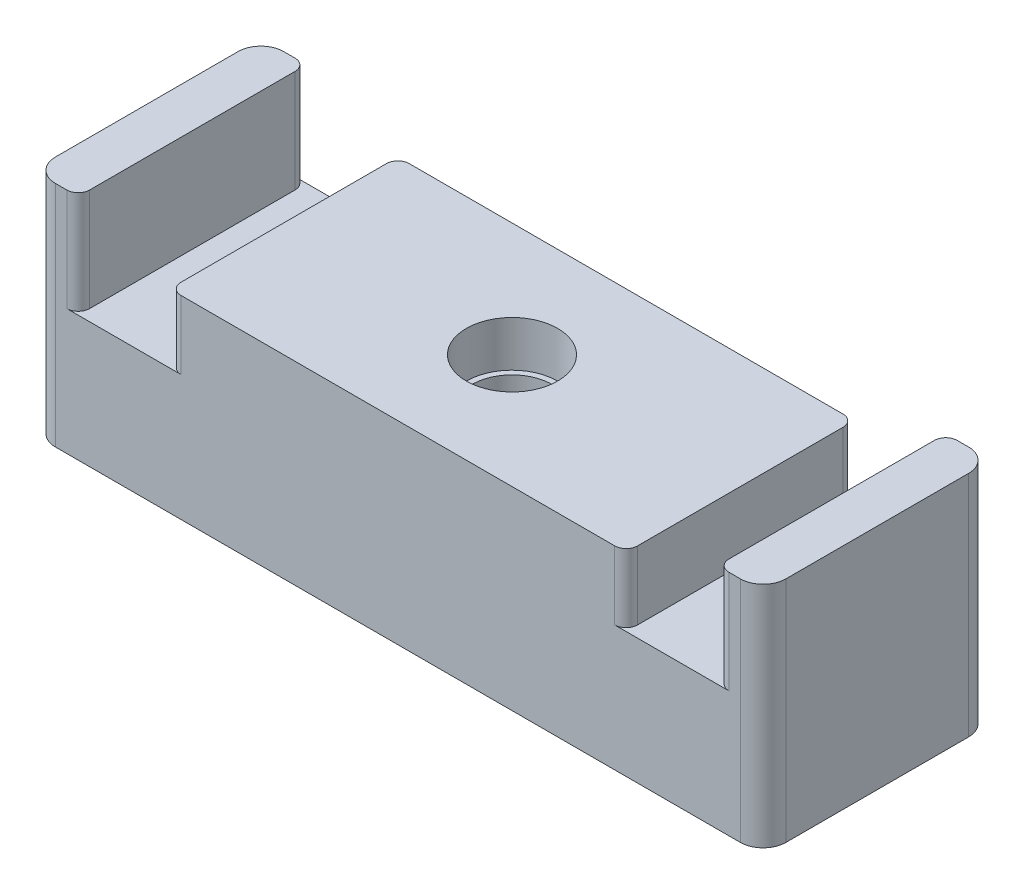
SolidWorks part; units mm, degrees
ref_plane "Front Plane" through (0, 0, 0) normal (0, 0, 1) x (1, 0, 0)
ref_plane "Top Plane" through (0, 0, 0) normal (0, 1, 0) x (1, 0, 0)
ref_plane "Right Plane" through (0, 0, 0) normal (1, 0, 0) x (0, 0, -1)
sketch "Sketch1" plane through (0, 0, 0) normal (0, 0, 1) x (1, 0, 0)
  line L0 (12, 0) -> (-12, 0) construction
  line L1 (-10, 2.5) -> (10, 2.5)
  line L2 (-16, 2.5) -> (-16, -7.5)
  line L3 (-16, -7.5) -> (16, -7.5)
  line L4 (16, 2.5) -> (16, -7.5)
  line L5 (-16, 2.5) -> (-14, 2.5)
  line L6 (14, 2.5) -> (16, 2.5)
  line L7 (-10, 0) -> (-10, 2.5)
  line L8 (10, 0) -> (10, 2.5)
  line L9 (-14, 2.5) -> (-14, 0)
  line L10 (14, 0) -> (14, 2.5)
  line L12 (14, 0) -> (10, 0) construction
  line L13 (14, 0) -> (14, -2)
  line L14 (14, -2) -> (10, -2)
  line L15 (10, 0) -> (10, -2)
  line L16 (-10, 0) -> (-14, 0) construction
  line L17 (-10, 0) -> (-10, -2)
  line L18 (-10, -2) -> (-14, -2)
  line L19 (-14, 0) -> (-14, -2)
  arc A0 (-14, 0) -> (-10, 0) centre (-12, 0) ccw construction
  arc A1 (10, 0) -> (14, 0) centre (12, 0) ccw construction
  point P8 (0, 3.5)
  dimension "D1" = 4
  dimension "D2" = 24
  dimension "D3" = 32
  dimension "D4" = 16
  dimension "D5" = 10
  dimension "D6" = 2.5
extrude "Boss-Extrude1" add sketch "Sketch1" along normal blind 10
sketch "Sketch2" plane through (0, 2.5, 0) normal (0, 1, 0) x (1, 0, 0)
  line L0 (-10, 0) -> (10, -10) construction
  circle A0 centre (0, -5) radius 1.75
  dimension "D1" = 3.5
extrude "Cut-Extrude1" cut sketch "Sketch2" against normal through all
fillet "Fillet2" radius 1 4 edges at (-16, -2.5, 0) (-16, -2.5, 10) (16, -2.5, 0) (16, -2.5, 10)
fillet "Fillet3" radius 0.5 8 edges at (-10, 0.25, 0) (-10, 0.25, 10) (14, 0.25, 0) (14, 0.25, 10) (10, 0.25, 0) (10, 0.25, 10) (-14, 0.25, 0) (-14, 0.25, 10)
sketch "Sketch4" plane through (0, 2.5, 0) normal (0, 1, 0) x (1, 0, 0)
  line L0 (9.5, 0) -> (-9.5, 0) construction
  line L1 (-10, 0) -> (10, 0)
  line L2 (-10, 0) -> (-10, -10)
  line L3 (-10, -10) -> (10, -10)
  line L4 (10, 0) -> (10, -10)
  line L5 (-10, -9.5) -> (-10, -0.5) construction
  line L6 (9.5, -10) -> (-9.5, -10) construction
  line L7 (10, -9.5) -> (10, -0.5) construction
extrude "Cut-Extrude3" cut sketch "Sketch4" against normal blind 1.5
sketch "Sketch5" plane through (0, 1, 0) normal (0, 1, 0) x (1, 0, 0)
  circle A0 centre (0, -5) radius 2
  dimension "D1" = 4
extrude "Cut-Extrude4" cut sketch "Sketch5" against normal blind 2
